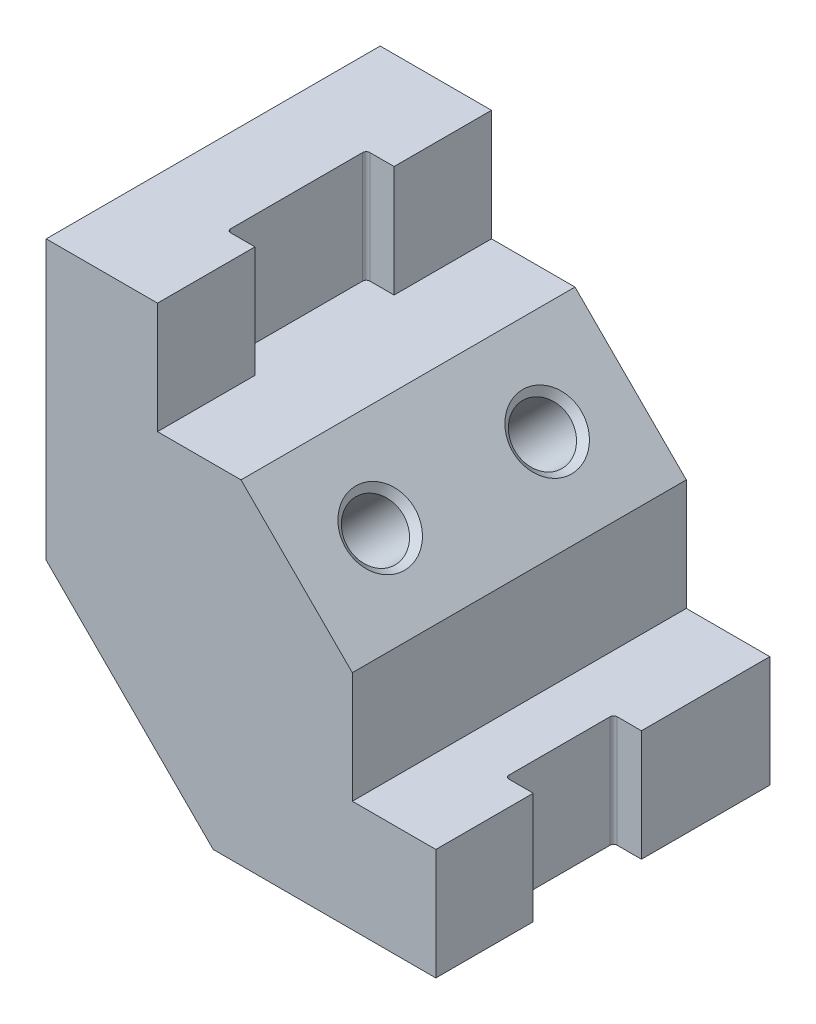
SolidWorks part; units mm, degrees
ref_plane "Front Plane" through (0, 0, 0) normal (0, 0, 1) x (1, 0, 0)
ref_plane "Top Plane" through (0, 0, 0) normal (0, 1, 0) x (1, 0, 0)
ref_plane "Right Plane" through (0, 0, 0) normal (1, 0, 0) x (0, 0, -1)
sketch "Sketch1" plane through (0, 0, 0) normal (0, 0, 1) x (1, 0, 0)
  line L2 (88.9, -101.6) -> (88.9, -76.2)
  line L3 (88.9, -76.2) -> (69.85, -76.2)
  line L4 (69.85, -76.2) -> (69.85, -50.8)
  line L5 (69.85, -50.8) -> (44.45, -25.4)
  line L6 (44.45, -25.4) -> (25.4, -25.4)
  line L7 (25.4, -25.4) -> (25.4, 0)
  line L8 (25.4, 0) -> (0, 0)
  line L9 (0, 0) -> (0, -63.5)
  line L10 (88.9, -101.6) -> (38.1, -101.6)
  line L11 (38.1, -101.6) -> (0, -63.5)
  point P3 (25.4, -12.7)
  dimension "D1" = 101.6
  dimension "D2" = 25.4
  dimension "D3" = 44.45
  dimension "D4" = 76.2
  dimension "D5" = 50.8
  dimension "D6" = 25.4
  dimension "D7" = 88.9
  dimension "D8" = 38.1
  dimension "D9" = 45
extrude "Boss-Extrude1" add sketch "Sketch1" along normal mid plane 76.2
sketch "Sketch2" plane through (9.525, 9.525, 0) normal (0.7071, 0.7071, 0) x (0, 0, -1)
  line L0 (0, 0) -> (0, -134.7038) construction
  line L1 (-38.1, -134.7038) -> (38.1, -134.7038) construction
  line L2 (-38.1, -85.3124) -> (38.1, -85.3124) construction
  circle A0 centre (19.05, -67.3546) radius 6.35
  circle A1 centre (-19.05, -67.3546) radius 6.35
  dimension "D3" = 12.7
  dimension "D1" = 17.9578
  dimension "D2" = 38.1
extrude "Cut-Extrude1" cut sketch "Sketch2" against normal through all and the other way through all
sketch "Sketch3" plane through (0, 0, 0) normal (0, 1, 0) x (1, 0, 0)
  line L0 (0, 0) -> (25.4, 0) construction
  line L1 (25.4, -38.1) -> (25.4, 38.1) construction
  line L3 (25.4, -15.875) -> (19.05, -15.875)
  line L4 (25.4, -15.875) -> (25.4, 15.875)
  line L5 (25.4, 15.875) -> (19.05, 15.875)
  line L6 (19.05, -15.875) -> (19.05, 15.875)
  point P9 (22.225, 15.875)
  dimension "D1" = 6.35
  dimension "D2" = 31.75
extrude "Cut-Extrude2" cut sketch "Sketch3" against normal up to vertex (25.4 mm away) up to point (25.4, -25.4, 38.1)
sketch "Sketch4" plane through (0, -76.2, 0) normal (0, 1, 0) x (1, 0, 0)
  line L0 (88.9, -38.1) -> (88.9, 38.1) construction
  line L1 (88.9, -15.875) -> (82.55, -15.875)
  line L2 (88.9, -15.875) -> (88.9, 8.8084)
  line L3 (88.9, 8.8084) -> (82.55, 8.8084)
  line L4 (82.55, -15.875) -> (82.55, 8.8084)
  line L5 (19.05, -15.875) -> (25.4, -15.875) construction
  point P6 (85.725, -15.875)
  point P9 (85.725, 8.8084)
extrude "Cut-Extrude3" cut sketch "Sketch4" against normal through all
fillet "Fillet1" radius 0.8128 4 edges at (82.55, -88.9, 15.875) (19.05, -12.7, 15.875) (82.55, -88.9, -8.8084) (19.05, -12.7, -15.875)
chamfer "Chamfer1" distance 1.524 angle 45 4 edges at (11.3868, -74.8868, -19.05) (11.3868, -74.8868, 19.05) (61.642, -42.592, -19.05) (61.642, -42.592, 19.05)
